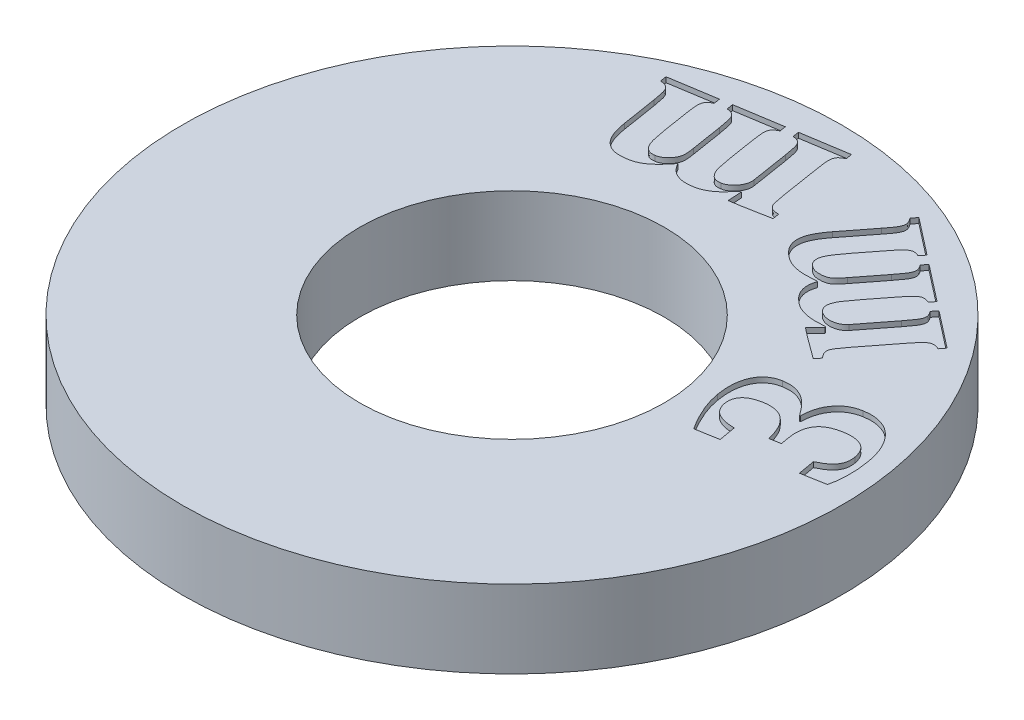
SolidWorks part; units mm, degrees
ref_plane "Front Plane" through (0, 0, 0) normal (0, 0, 1) x (1, 0, 0)
ref_plane "Top Plane" through (0, 0, 0) normal (0, 1, 0) x (1, 0, 0)
ref_plane "Right Plane" through (0, 0, 0) normal (1, 0, 0) x (0, 0, -1)
sketch "Sketch1" plane through (0, 0, 0) normal (0, 1, 0) x (1, 0, 0)
  circle A0 centre (0, 0) radius 12.7
  dimension "D1" = 25.4
extrude "Boss-Extrude1" add sketch "Sketch1" along normal blind 3
sketch "Sketch2" plane through (0, 0, 0) normal (0, -1, 0) x (-1, 0, 0)
  circle A0 centre (0, 0) radius 5.8674
  dimension "D1" = 11.7348
extrude "Cut-Extrude1" cut sketch "Sketch2" against normal through all
sketch "Sketch4" plane through (0, 3, 0) normal (0, 1, 0) x (1, 0, 0)
  circle A0 centre (0, 0) radius 12.0429 construction
  text T0 "<b>3mm</b>" font "Cambria" height 5.08
extrude "Cut-Extrude2" cut sketch "Sketch4" against normal blind 0.2
